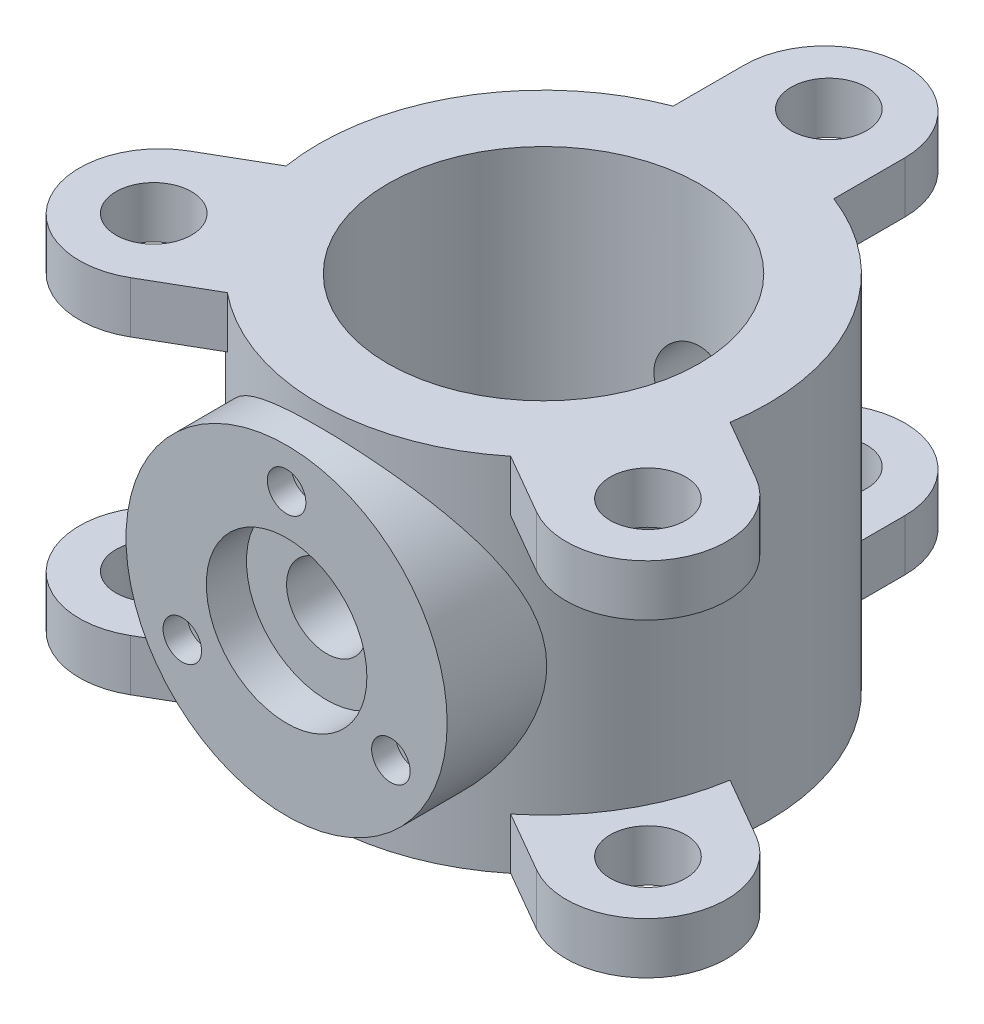
SolidWorks part; units mm, degrees
ref_plane "Front Plane" through (0, 0, 0) normal (0, 0, 1) x (1, 0, 0)
ref_plane "Top Plane" through (0, 0, 0) normal (0, 1, 0) x (1, 0, 0)
ref_plane "Right Plane" through (0, 0, 0) normal (1, 0, 0) x (0, 0, -1)
sketch "Sketch1" plane through (0, 0, 0) normal (0, 1, 0) x (1, 0, 0)
  circle A0 centre (0, 0) radius 140
  circle A1 centre (0, 0) radius 97
  dimension "D1" = 280
  dimension "D2" = 194
extrude "Boss-Extrude1" add sketch "Sketch1" along normal blind 225
sketch "Sketch3" plane through (0, 225, 0) normal (0, 1, 0) x (1, 0, 0)
  line L1 (-50, 175) -> (50, 175) construction
  line L2 (-50, 175) -> (-50, 101.5287)
  line L3 (-50, 101.5287) -> (50, 101.5287)
  line L4 (50, 175) -> (50, 101.5287)
  line L5 (-50, 175) -> (50, 101.5287) construction
  line L6 (-50, 101.5287) -> (50, 175) construction
  arc A1 (50, 175) -> (-50, 175) centre (0, 175) ccw
  circle A2 centre (0, 177.7026) radius 23.5
  point P0 (0, 138.2643)
  dimension "D2" = 47
  dimension "D1" = 175
  dimension "D3" = 100
extrude "Boss-Extrude3" add sketch "Sketch3" against normal blind 32
pattern_circular "CirPattern1" count 3 over 360 about axis through (0, 0, 0) along (0, 1, 0) of "Boss-Extrude3"
ref_plane "Plane1" through (0, 112.5, 0) normal (0, 1, 0) x (1, 0, 0)
mirror "Mirror1" about plane through (0, 112.5, 0) normal (0, 1, 0) of "CirPattern1", "Boss-Extrude3"
ref_plane "Plane2" through (0, 0, 160) normal (0, 0, 1) x (1, 0, 0)
sketch "Sketch4" plane through (0, 0, 160) normal (0, 0, 1) x (1, 0, 0)
  line L0 (-88.2475, 0) -> (88.2475, 0) construction
  circle A0 centre (0, 112.5) radius 100
  dimension "D1" = 200
  dimension "D2" = 112.5
extrude "Boss-Extrude4" add sketch "Sketch4" against normal up to next
sketch "Sketch5" plane through (0, 0, 160) normal (0, 0, 1) x (1, 0, 0)
  circle A0 centre (0, 112.5) radius 50
  dimension "D1" = 100
extrude "Cut-Extrude1" cut sketch "Sketch5" against normal blind 25
sketch "Sketch6" plane through (0, 0, 160) normal (0, 0, 1) x (1, 0, 0)
  circle A0 centre (0, 112.5) radius 25
  dimension "D1" = 50
extrude "Cut-Extrude2" cut sketch "Sketch6" against normal through all
sketch "Sketch7" plane through (0, 0, 160) normal (0, 0, 1) x (1, 0, 0)
  circle A0 centre (0, 112.5) radius 75 construction
  circle A1 centre (0, 187.5) radius 12
  circle A2 centre (64.9519, 75) radius 12
  circle A3 centre (-64.9519, 75) radius 12
  dimension "D1" = 150
  dimension "D2" = 24
  dimension "D4" = 37.5
  dimension "D5" = 37.5
  dimension "D3" = 3
extrude "Cut-Extrude3" cut sketch "Sketch7" against normal blind 15
